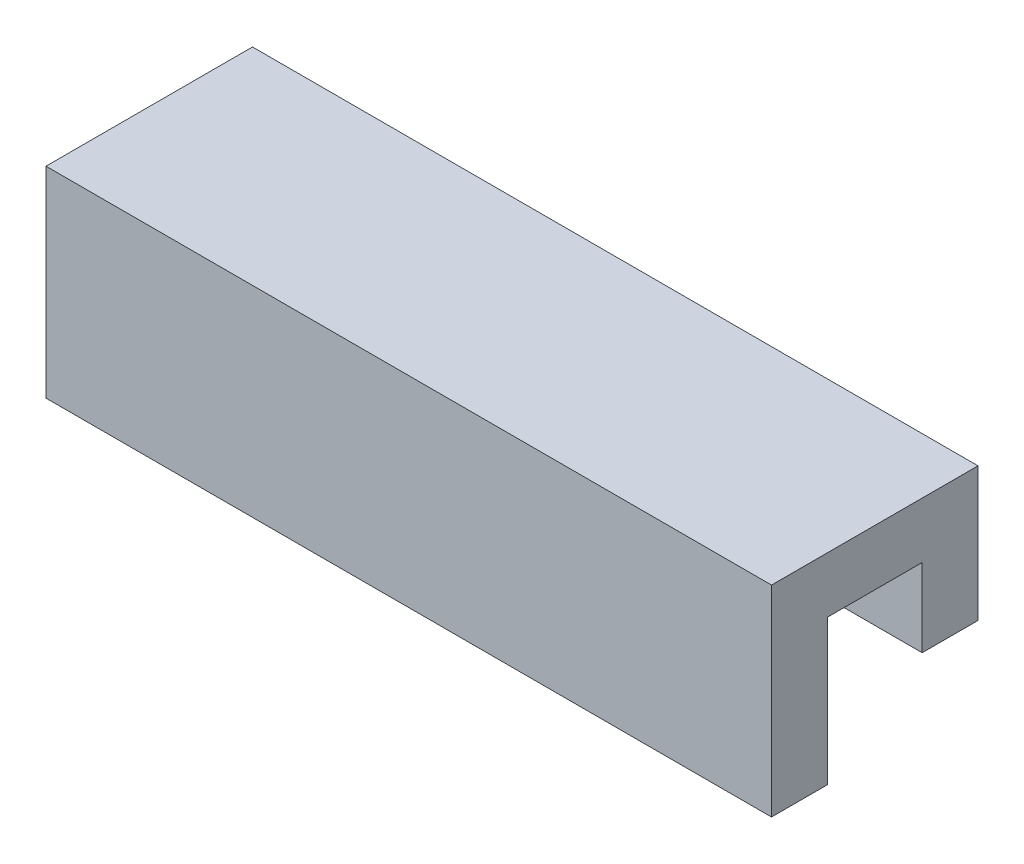
SolidWorks part; units mm, degrees
ref_plane "정면" through (0, 0, 0) normal (0, 0, 1) x (1, 0, 0)
ref_plane "윗면" through (0, 0, 0) normal (0, 1, 0) x (1, 0, 0)
ref_plane "우측면" through (0, 0, 0) normal (1, 0, 0) x (0, 0, -1)
sketch "스케치2" plane through (0, 0, 0) normal (0, 0, 1) x (1, 0, 0)
  line L1 (65, -18) -> (-65, -18)
  line L2 (65, -18) -> (65, 18)
  line L3 (65, 18) -> (-65, 18)
  line L4 (-65, -18) -> (-65, 18)
  line L5 (65, -18) -> (-65, 18) construction
  line L6 (65, 18) -> (-65, -18) construction
  point P0 (0, 0)
  dimension "D1" = 130
  dimension "D2" = 36
extrude "보스-돌출1" add sketch "스케치2" along normal blind 37
sketch "스케치4" plane through (0, 0, 0) normal (0, 1, 0) x (1, 0, 0)
  line L0 (0, 0) -> (0, -63.4145) construction
  line L1 (-65, -18.5) -> (76.3477, -18.5) construction
  line L2 (-65, -37) -> (-65, 0) construction
  line L4 (65, -27.0064) -> (-65, -27.0064)
  line L5 (65, -27.0064) -> (65, -10.0064)
  line L6 (65, -10.0064) -> (-65, -10.0064)
  line L7 (-65, -27.0064) -> (-65, -10.0064)
  line L8 (65, -27.0064) -> (-65, -10.0064) construction
  line L9 (65, -10.0064) -> (-65, -27.0064) construction
  point P7 (0, -18.5064)
  dimension "D1" = 17
extrude "컷-돌출1" cut sketch "스케치4" along normal blind 26 from surface at -18 starting at face at (0, -18, 18.5)
sketch "스케치5" plane through (0, 0, 0) normal (0, 1, 0) x (1, 0, 0)
  line L0 (65, -37) -> (65, 0) construction
  line L1 (-65, 0) -> (65, 0)
  line L2 (-65, 0) -> (-65, -12)
  line L3 (-65, -12) -> (65, -12)
  line L4 (65, 0) -> (65, -12)
  dimension "D1" = 12
extrude "컷-돌출2" cut sketch "스케치5" along normal blind 12 from offset 18
